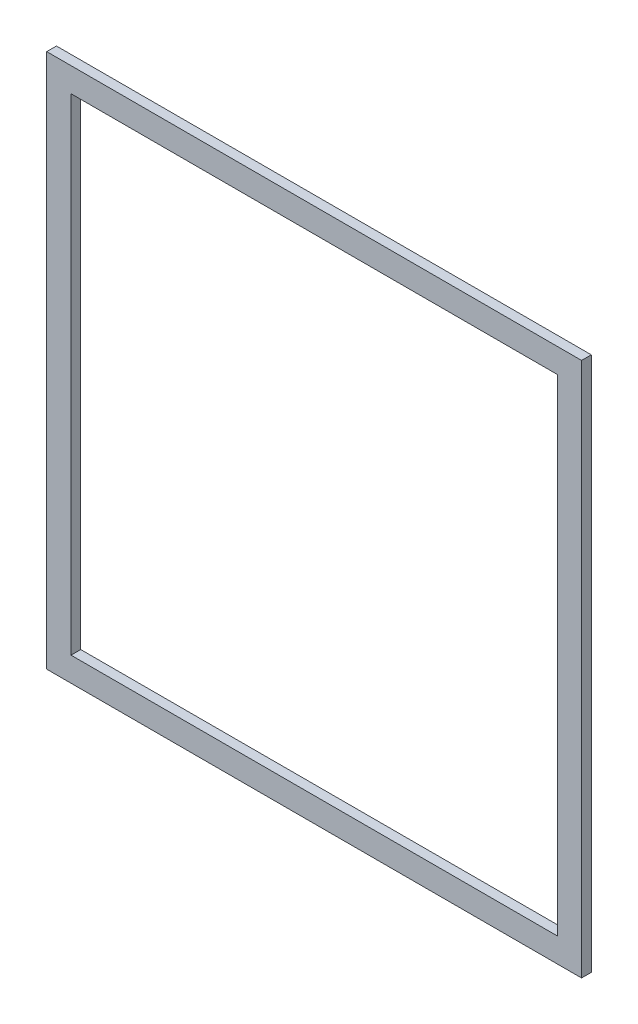
SolidWorks part; units mm, degrees
ref_plane "Front Plane" through (0, 0, 0) normal (0, 0, 1) x (1, 0, 0)
ref_plane "Top Plane" through (0, 0, 0) normal (0, 1, 0) x (1, 0, 0)
ref_plane "Right Plane" through (0, 0, 0) normal (1, 0, 0) x (0, 0, -1)
sketch "Sketch1" plane through (0, 0, 0) normal (0, 0, 1) x (1, 0, 0)
  line L1 (275, 275) -> (-275, 275)
  line L2 (275, 275) -> (275, -275)
  line L3 (275, -275) -> (-275, -275)
  line L4 (-275, 275) -> (-275, -275)
  line L5 (-250, -250) -> (250, -250)
  line L6 (-250, -250) -> (-250, 250)
  line L7 (-250, 250) -> (250, 250)
  line L8 (250, -250) -> (250, 250)
  point P8 (-250, 0)
  point P10 (-275, 0)
  point P11 (0, 250)
  point P13 (0, 275)
  dimension "D1" = 500
  dimension "D2" = 550
extrude "Boss-Extrude1" add sketch "Sketch1" along normal blind 10
